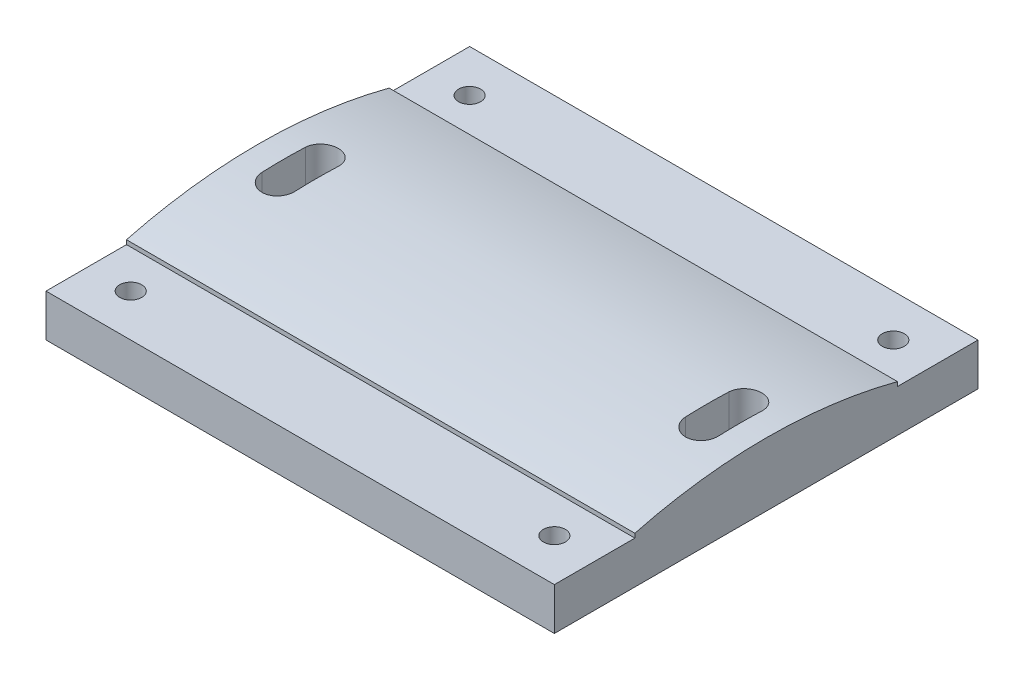
SolidWorks part; units mm, degrees
ref_plane "前视基准面" through (0, 0, 0) normal (0, 0, 1) x (1, 0, 0)
ref_plane "上视基准面" through (0, 0, 0) normal (0, 1, 0) x (1, 0, 0)
ref_plane "右视基准面" through (0, 0, 0) normal (1, 0, 0) x (0, 0, -1)
sketch "草图1" plane through (0, 0, 0) normal (0, 1, 0) x (1, 0, 0)
  line L1 (0, 500) -> (600, 500)
  line L2 (0, 500) -> (0, 0)
  line L3 (0, 0) -> (600, 0)
  line L4 (600, 500) -> (600, 0)
  dimension "D1" = 600
  dimension "D2" = 500
extrude "凸台-拉伸1" add sketch "草图1" along normal blind 75
sketch "草图3" plane through (600, 0, 0) normal (1, 0, 0) x (0, 0, -1)
  line L0 (250, -925) -> (250, 49075) construction
  line L1 (0, 75) -> (500, 75) construction
  line L2 (405, 55) -> (405, 50)
  line L3 (405, 50) -> (500, 50)
  line L4 (500, 75) -> (500, 0) construction
  line L5 (500, 50) -> (500, 75)
  line L6 (500, 75) -> (250, 75)
  arc A0 (405, 55) -> (250, 75) centre (250, -535.625) ccw
  point P5 (250, 75)
  dimension "D1" = 20
  dimension "D2" = 5
  dimension "D3" = 95
extrude "切除-拉伸1" cut sketch "草图3" against normal through all
sketch "草图4" plane through (600, 0, 0) normal (1, 0, 0) x (0, 0, -1)
  line L0 (250, -1000) -> (250, 49000) construction
  line L1 (0, 0) -> (500, 0) construction
  line L2 (0, 75) -> (250, 75) construction
  line L3 (-550, 55) -> (49450, 55) construction
  line L4 (0, 75) -> (0, 0) construction
  line L5 (0, 75) -> (0, 50)
  line L6 (0, 50) -> (95, 50)
  line L7 (0, 75) -> (250, 75)
  line L8 (95, 50) -> (95, 55)
  line L9 (405, 50) -> (500, 50) construction
  arc A0 (250, 75) -> (95, 55) centre (250, -535.625) ccw
  arc A1 (405, 55) -> (250, 75) centre (250, -535.625) ccw construction
  point P5 (250, 0)
  dimension "D1" = 95
extrude "切除-拉伸2" cut sketch "草图4" against normal through all
sketch "草图5" plane through (0, 50, 0) normal (0, 1, 0) x (1, 0, 0)
  line L0 (-930.8909, 450) -> (49069.1091, 450) construction
  line L1 (-945.164, 50) -> (49054.836, 50) construction
  line L2 (50, -474.9785) -> (50, 49525.0215) construction
  line L3 (550, -487.5724) -> (550, 49512.4276) construction
  line L4 (0, 405) -> (0, 500) construction
  line L5 (0, 500) -> (600, 500) construction
  line L6 (600, 0) -> (600, 95) construction
  line L7 (0, 0) -> (600, 0) construction
  circle A0 centre (50, 450) radius 13
  circle A1 centre (550, 450) radius 13
  circle A2 centre (50, 50) radius 13
  circle A3 centre (550, 50) radius 13
  dimension "D5" = 26
  dimension "D1" = 50
  dimension "D2" = 50
  dimension "D3" = 50
  dimension "D4" = 50
extrude "切除-拉伸3" cut sketch "草图5" against normal through all
sketch "草图6" plane through (0, 0, 0) normal (0, -1, 0) x (1, 0, 0)
  line L0 (-1000, -250) -> (49000, -250) construction
  line L1 (50, -1050) -> (50, 48950) construction
  line L2 (550, -1050) -> (550, 48950) construction
  line L3 (-400, -250) -> (49600, -250) construction
  line L4 (30.5, -224.5) -> (30.5, -275.5)
  line L5 (69.5, -224.5) -> (69.5, -275.5)
  line L6 (-950, -205) -> (49050, -205) construction
  line L7 (-915.5273, -295) -> (49084.4727, -295) construction
  line L8 (600, 0) -> (600, -500) construction
  arc A0 (30.5, -224.5) -> (69.5, -224.5) centre (50, -224.5) cw
  arc A1 (69.5, -275.5) -> (30.5, -275.5) centre (50, -275.5) cw
  point P24 (600, -250)
  dimension "D1" = 45
  dimension "D2" = 45
  dimension "D3" = 39
extrude "切除-拉伸4" cut sketch "草图6" against normal through all
pattern_linear "阵列(线性)1" count 2 spacing 500 along (1, 0, 0) of "切除-拉伸4"
